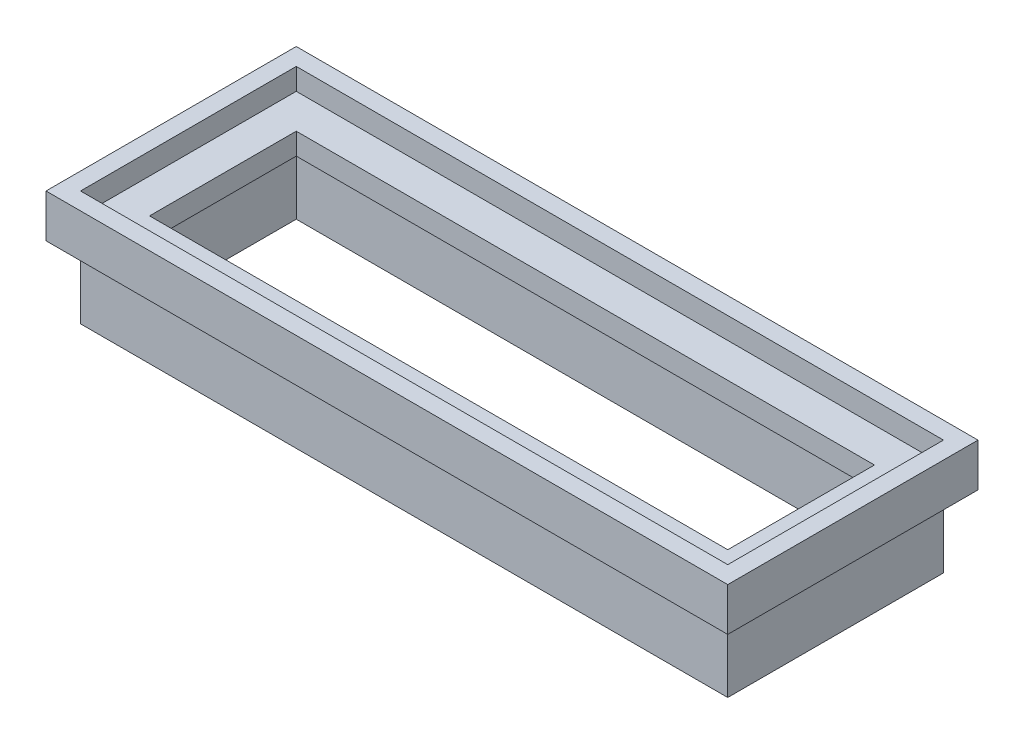
SolidWorks part; units mm, degrees
ref_plane "Front Plane" through (0, 0, 0) normal (0, 0, 1) x (1, 0, 0)
ref_plane "Top Plane" through (0, 0, 0) normal (0, 1, 0) x (1, 0, 0)
ref_plane "Right Plane" through (0, 0, 0) normal (1, 0, 0) x (0, 0, -1)
sketch "Sketch2" plane through (0, 0, 0) normal (0, 1, 0) x (1, 0, 0)
  line L1 (-26.8763, 8.9474) -> (15.7237, 8.9474)
  line L2 (-26.8763, 8.9474) -> (-26.8763, -3.6526)
  line L3 (-26.8763, -3.6526) -> (15.7237, -3.6526)
  line L4 (15.7237, 8.9474) -> (15.7237, -3.6526)
  dimension "D1" = 12.6
  dimension "D2" = 42.6
extrude "Extrude-Thin1" add sketch "Sketch2" along normal blind 5 thin contours L1 L4 L3 L2 thin type one direction wall 1.2
sketch "Sketch5" plane through (0, 5, 0) normal (0, 1, 0) x (1, 0, 0)
  line L0 (-28.0763, 10.1474) -> (16.9237, 10.1474) construction
  line L1 (-28.0763, 10.1474) -> (-25.6763, 10.1474)
  line L2 (-25.6763, 10.1474) -> (-25.6763, 7.7474) construction
  line L3 (16.9237, -4.8526) -> (14.5237, -4.8526) construction
  line L4 (-28.0763, -4.8526) -> (16.9237, -4.8526) construction
  line L5 (14.5237, -4.8526) -> (14.5237, -2.4526) construction
  line L7 (-25.6763, 7.7474) -> (14.5237, 7.7474)
  line L8 (-25.6763, 7.7474) -> (-25.6763, -2.4526)
  line L9 (-25.6763, -2.4526) -> (14.5237, -2.4526)
  line L10 (14.5237, 7.7474) -> (14.5237, -2.4526)
  dimension "D1" = 2.4
extrude "Extrude-Thin3" add sketch "Sketch5" along normal blind 3 thin contours L7 L10 L9 L8
sketch "Sketch6" plane through (0, 8, 0) normal (0, 1, 0) x (1, 0, 0)
  line L0 (-29.2763, 11.3474) -> (-28.0763, 11.3474) construction
  line L1 (-29.2763, 11.3474) -> (18.1237, 11.3474) construction
  line L2 (-28.0763, 11.3474) -> (-28.0763, 10.1474) construction
  line L3 (18.1237, -6.0526) -> (16.9237, -6.0526) construction
  line L4 (-29.2763, -6.0526) -> (18.1237, -6.0526) construction
  line L5 (16.9237, -6.0526) -> (16.9237, -4.8526) construction
  line L7 (-28.0763, 10.1474) -> (16.9237, 10.1474)
  line L8 (-28.0763, 10.1474) -> (-28.0763, -4.8526)
  line L9 (-28.0763, -4.8526) -> (16.9237, -4.8526)
  line L10 (16.9237, 10.1474) -> (16.9237, -4.8526)
extrude "Cut-Extrude2" cut sketch "Sketch6" against normal blind 1.5 contours L8 L9 L10 L7
